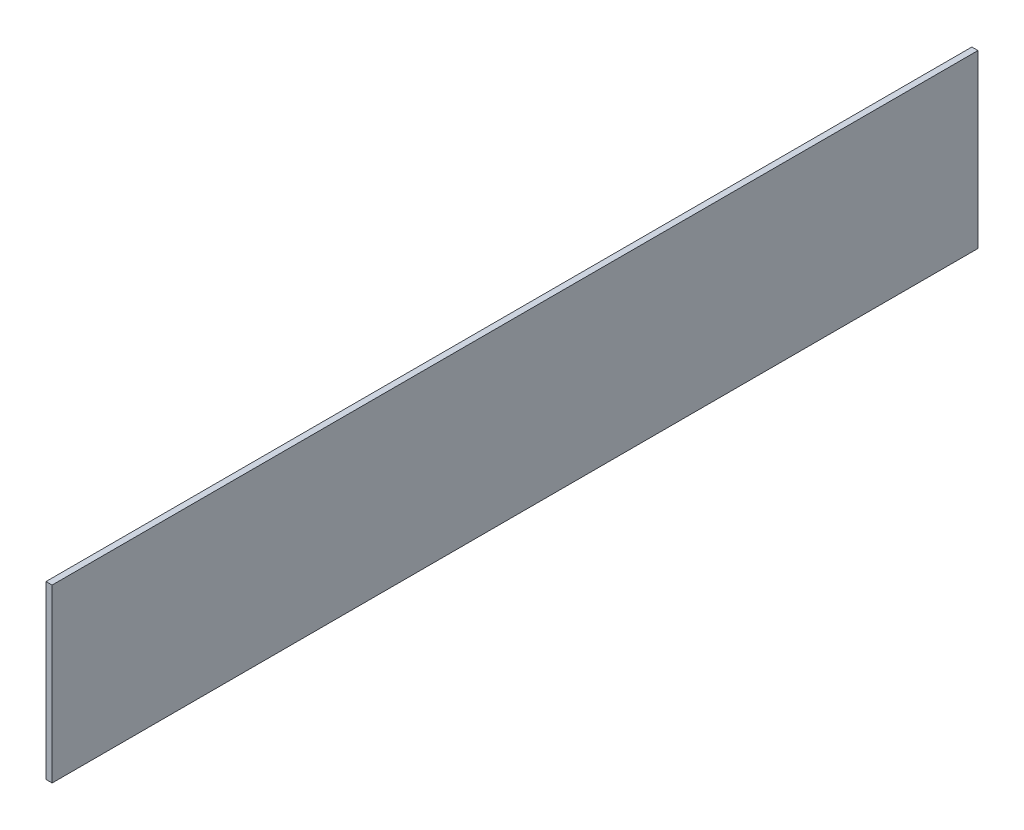
SolidWorks part; units mm, degrees
material "PC High Viscosity"
ref_plane "Front Plane" through (0, 0, 0) normal (0, 0, 1) x (1, 0, 0)
ref_plane "Top Plane" through (0, 0, 0) normal (0, 1, 0) x (1, 0, 0)
ref_plane "Right Plane" through (0, 0, 0) normal (1, 0, 0) x (0, 0, -1)
sketch "Sketch1" plane through (0, 0, 0) normal (1, 0, 0) x (0, 0, -1)
  line L1 (120.015, 22.225) -> (-120.015, 22.225)
  line L2 (120.015, 22.225) -> (120.015, -22.225)
  line L3 (120.015, -22.225) -> (-120.015, -22.225)
  line L4 (-120.015, 22.225) -> (-120.015, -22.225)
  line L5 (120.015, 22.225) -> (-120.015, -22.225) construction
  line L6 (120.015, -22.225) -> (-120.015, 22.225) construction
  point P0 (0, 0)
  dimension "D1" = 44.45
  dimension "D2" = 240.03
extrude "Boss-Extrude1" add sketch "Sketch1" along normal blind 1.5875
